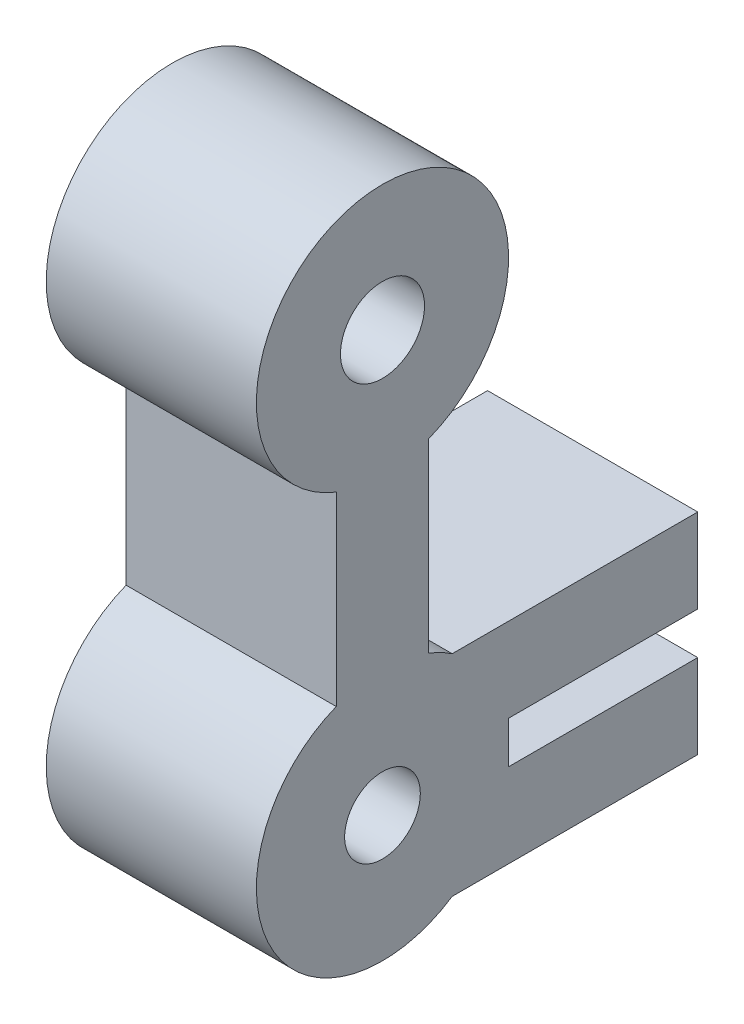
SolidWorks part; units mm, degrees
ref_plane "Front Plane" through (0, 0, 0) normal (1, 0, 0) x (0, 1, 0)
ref_plane "Top Plane" through (0, 0, 0) normal (0, 0, 1) x (0, 1, 0)
ref_plane "Right Plane" through (0, 0, 0) normal (0, 1, 0) x (-1, 0, 0)
sketch "Sketch1" plane through (0, 0, 0) normal (1, 0, 0) x (0, 1, 0)
  line L0 (-300.6135, 0) -> (290.4478, 0) construction
  line L1 (0, 281.3713) -> (0, -279.193) construction
  line L2 (-25, -16.5831) -> (-25, -75)
  line L3 (-25, -75) -> (-5, -75)
  line L4 (-5, -75) -> (-5, -30)
  line L5 (-5, -30) -> (5, -30)
  line L6 (5, -75) -> (5, -30)
  line L7 (25, -75) -> (5, -75)
  line L8 (25, -16.5831) -> (25, -75)
  line L10 (72.0894, 11) -> (27.9106, 11)
  line L11 (72.0894, -11) -> (27.9106, -11)
  circle A0 centre (0, 0) radius 9
  arc A1 (25, -16.5831) -> (27.9106, -11) centre (0, 0) ccw
  arc A2 (72.0894, -11) -> (72.0894, 11) centre (100, 0) ccw
  circle A5 centre (100, 0) radius 10
  arc A6 (27.9106, 11) -> (-25, -16.5831) centre (0, 0) ccw
  point P17 (0, -30)
  point P24 (100, 0)
  dimension "D1" = 60
  dimension "D2" = 18
  dimension "D7" = 60
  dimension "D9" = 20
  dimension "D3" = 75
  dimension "D4" = 45
  dimension "D5" = 20
  dimension "D6" = 50
  dimension "D8" = 100
  dimension "D10" = 22
extrude "Boss-Extrude1" add sketch "Sketch1" against normal blind 50
